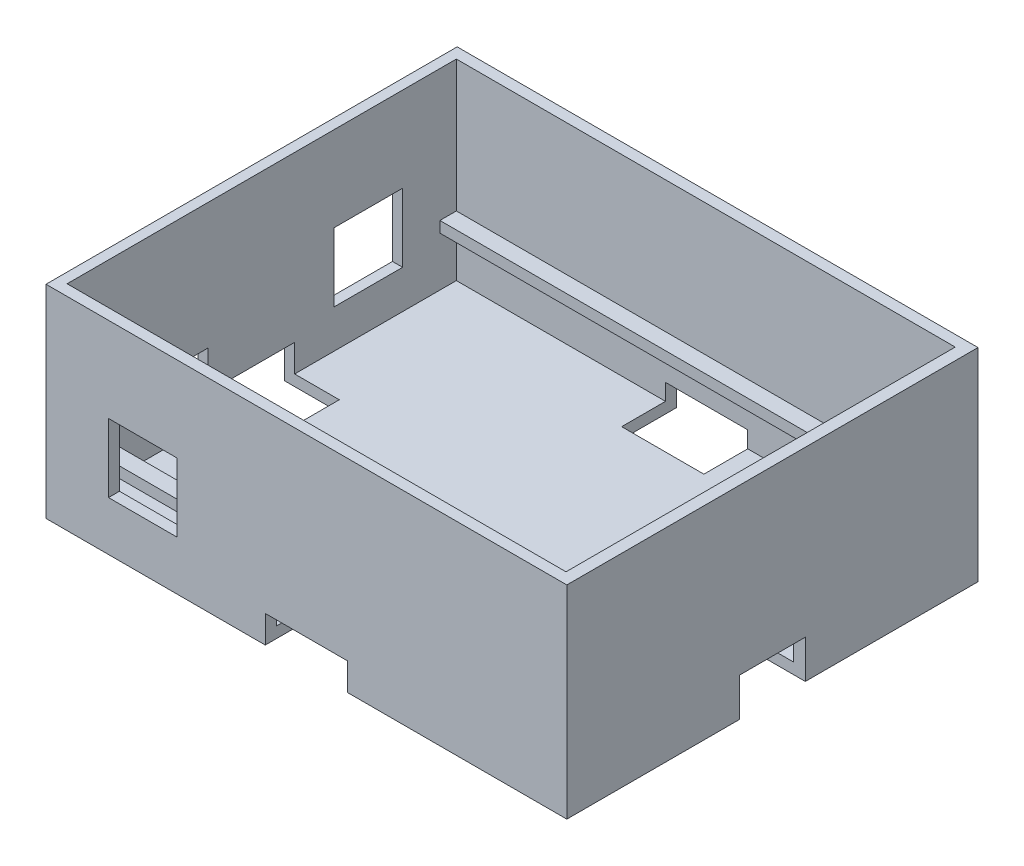
SolidWorks part; units mm, degrees
ref_plane "Front Plane" through (0, 0, 0) normal (0, 0, 1) x (1, 0, 0)
ref_plane "Top Plane" through (0, 0, 0) normal (0, 1, 0) x (1, 0, 0)
ref_plane "Right Plane" through (0, 0, 0) normal (1, 0, 0) x (0, 0, -1)
sketch "Sketch1" plane through (0, 0, 0) normal (0, 1, 0) x (1, 0, 0)
  line L1 (-47.5, 37.5) -> (47.5, 37.5)
  line L2 (-47.5, 37.5) -> (-47.5, -37.5)
  line L3 (-47.5, -37.5) -> (47.5, -37.5)
  line L4 (47.5, 37.5) -> (47.5, -37.5)
  line L5 (-47.5, 37.5) -> (47.5, -37.5) construction
  line L6 (-47.5, -37.5) -> (47.5, 37.5) construction
  point P0 (0, 0)
  dimension "D1" = 75
  dimension "D2" = 95
extrude "Boss-Extrude1" add sketch "Sketch1" along normal blind 2
sketch "Sketch2" plane through (0, 2, 0) normal (0, 1, 0) x (1, 0, 0)
  line L0 (-47.5, 37.5) -> (-47.5, -37.5)
  line L1 (-47.5, -37.5) -> (47.5, -37.5)
  line L2 (47.5, -37.5) -> (47.5, 37.5)
  line L3 (47.5, 37.5) -> (-47.5, 37.5)
  line L4 (-45.6485, 35.5) -> (-45.6485, -35.5)
  line L5 (-45.6485, -35.5) -> (45.3515, -35.5)
  line L6 (45.3515, -35.5) -> (45.3515, 35.5)
  line L7 (45.3515, 35.5) -> (-45.6485, 35.5)
  line L8 (47.5, -37.5) -> (47.5, 37.5) construction
  point P12 (-45.6485, 0)
  point P13 (45.3515, 0)
  dimension "D1" = 71
  dimension "D2" = 91
  dimension "D3" = 2.1485
extrude "Boss-Extrude2" add sketch "Sketch2" along normal blind 35
sketch "Sketch3" plane through (0, 0, 37.5) normal (0, 0, 1) x (1, 0, 0)
  line L0 (-47.5, 37) -> (-47.5, 0) construction
  line L1 (-36.1, 21.5) -> (-23.6, 21.5)
  line L2 (-36.1, 21.5) -> (-36.1, 9)
  line L3 (-36.1, 9) -> (-23.6, 9)
  line L4 (-23.6, 21.5) -> (-23.6, 9)
  line L5 (-47.5, 0) -> (47.5, 0) construction
  dimension "D1" = 11.4
  dimension "D2" = 9
  dimension "D3" = 12.5
  dimension "D4" = 12.5
extrude "Cut-Extrude1" cut sketch "Sketch3" against normal blind 10
sketch "Sketch4" plane through (-47.5, 0, 0) normal (-1, 0, 0) x (0, 0, 1)
  line L0 (-37.5, 37) -> (-37.5, 0) construction
  line L1 (-25.7, 21.5) -> (-13.2, 21.5)
  line L2 (-25.7, 21.5) -> (-25.7, 9)
  line L3 (-25.7, 9) -> (-13.2, 9)
  line L4 (-13.2, 21.5) -> (-13.2, 9)
  line L5 (-37.5, 0) -> (37.5, 0) construction
  dimension "D1" = 11.8
  dimension "D2" = 9
  dimension "D3" = 12.5
  dimension "D4" = 12.5
extrude "Cut-Extrude2" cut sketch "Sketch4" against normal blind 10
sketch "Sketch5" plane through (-47.5, 0, 0) normal (-1, 0, 0) x (0, 0, 1)
  line L0 (-25.7, 9) -> (-13.2, 9) construction
  line L1 (9.8, 14) -> (19.3, 14)
  line L2 (9.8, 14) -> (9.8, 9)
  line L3 (9.8, 9) -> (19.3, 9)
  line L4 (19.3, 14) -> (19.3, 9)
  dimension "D1" = 23
  dimension "D2" = 5
  dimension "D3" = 9.5
extrude "Cut-Extrude3" cut sketch "Sketch5" against normal blind 10
sketch "Sketch6" plane through (0, 0, -37.5) normal (0, 0, -1) x (-1, 0, 0)
  line L0 (-47.5, 0) -> (47.5, 0) construction
  line L1 (-7.5, 5) -> (7.5, 5)
  line L2 (-7.5, 5) -> (-7.5, 0)
  line L3 (-7.5, 0) -> (7.5, 0)
  line L4 (7.5, 5) -> (7.5, 0)
  point P6 (0, 5)
  dimension "D1" = 5
  dimension "D2" = 15
extrude "Cut-Extrude4" cut sketch "Sketch6" against normal blind 10
mirror "Mirror1" about plane through (0, 0, 0) normal (0, 0, 1) of "Cut-Extrude4"
sketch "Sketch7" plane through (-47.5, 0, 0) normal (-1, 0, 0) x (0, 0, 1)
  line L0 (-37.5, 0) -> (37.5, 0) construction
  line L1 (6, 7) -> (-6, 7)
  line L2 (6, 7) -> (6, 0)
  line L3 (6, 0) -> (-6, 0)
  line L4 (-6, 7) -> (-6, 0)
  line L5 (-37.5, 37) -> (37.5, 37) construction
  point P8 (0, 37)
  point P9 (0, 0)
  dimension "D1" = 7
  dimension "D2" = 12
extrude "Cut-Extrude5" cut sketch "Sketch7" against normal blind 10
mirror "Mirror2" about plane through (0, 0, 0) normal (1, 0, 0) of "Cut-Extrude5"
sketch "Sketch8" plane through (0, 0, -35.5) normal (0, 0, 1) x (1, 0, 0)
  line L0 (-45.6485, 21.5) -> (-45.6485, 9) construction
  line L1 (-45.6485, 13) -> (45.3515, 13)
  line L2 (-45.6485, 13) -> (-45.6485, 11)
  line L3 (-45.6485, 11) -> (45.3515, 11)
  line L4 (45.3515, 13) -> (45.3515, 11)
  line L5 (45.3515, 37) -> (45.3515, 2) construction
  line L6 (45.3515, 2) -> (7.5, 2) construction
  dimension "D1" = 9
  dimension "D2" = 2
extrude "Boss-Extrude3" add sketch "Sketch8" along normal blind 3
mirror "Mirror3" about plane through (0, 0, 0) normal (0, 0, 1) of "Boss-Extrude3"
